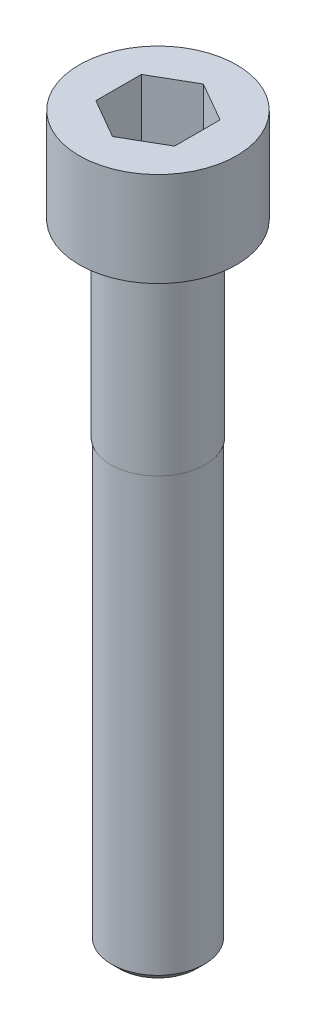
SolidWorks part; units mm, degrees
ref_plane "Plan de face" through (0, 0, 0) normal (0, 0, 1) x (1, 0, 0)
ref_plane "Plan de dessus" through (0, 0, 0) normal (0, 1, 0) x (1, 0, 0)
ref_plane "Plan de droite" through (0, 0, 0) normal (1, 0, 0) x (0, 0, -1)
sketch "Esquisse1" plane through (0, 0, 0) normal (0, 0, 1) x (1, 0, 0)
  line L0 (0, 0) -> (-2.45, 0)
  line L1 (-2.45, 0) -> (-2.95, 0.5)
  line L2 (-2.95, 0.5) -> (-2.95, 28)
  line L3 (-2.95, 28) -> (-3, 28)
  line L4 (-3, 28) -> (-3, 40)
  line L5 (-3, 40) -> (-5, 40)
  line L6 (-5, 40) -> (-5, 46)
  line L7 (-5, 46) -> (0, 46)
  line L8 (0, 46) -> (0, 0) construction
  line L9 (0, 0) -> (0, 46)
  point P12 (-2.6701, -0.015)
  dimension "D1" = 10
  dimension "D2" = 6
  dimension "D3" = 12
  dimension "D4" = 28
  dimension "D5" = 6
  dimension "D6" = 2.95
  dimension "D7" = 0.5
  dimension "D8" = 0.5
revolve "Révolution1" add sketch "Esquisse1" angle 360 about L8
sketch "Esquisse2" plane through (0, 46, 0) normal (0, 1, 0) x (1, 0, 0)
  line L1 (2.5, -1.4434) -> (2.5, 1.4434)
  line L2 (2.5, 1.4434) -> (0, 2.8868)
  line L3 (0, 2.8868) -> (-2.5, 1.4434)
  line L4 (-2.5, 1.4434) -> (-2.5, -1.4434)
  line L5 (-2.5, -1.4434) -> (0, -2.8868)
  line L6 (0, -2.8868) -> (2.5, -1.4434)
  circle A0 centre (0, 0) radius 2.5 construction
  dimension "D1" = 5
extrude "Enlèv. mat.-Extru.1" cut sketch "Esquisse2" against normal blind 4
